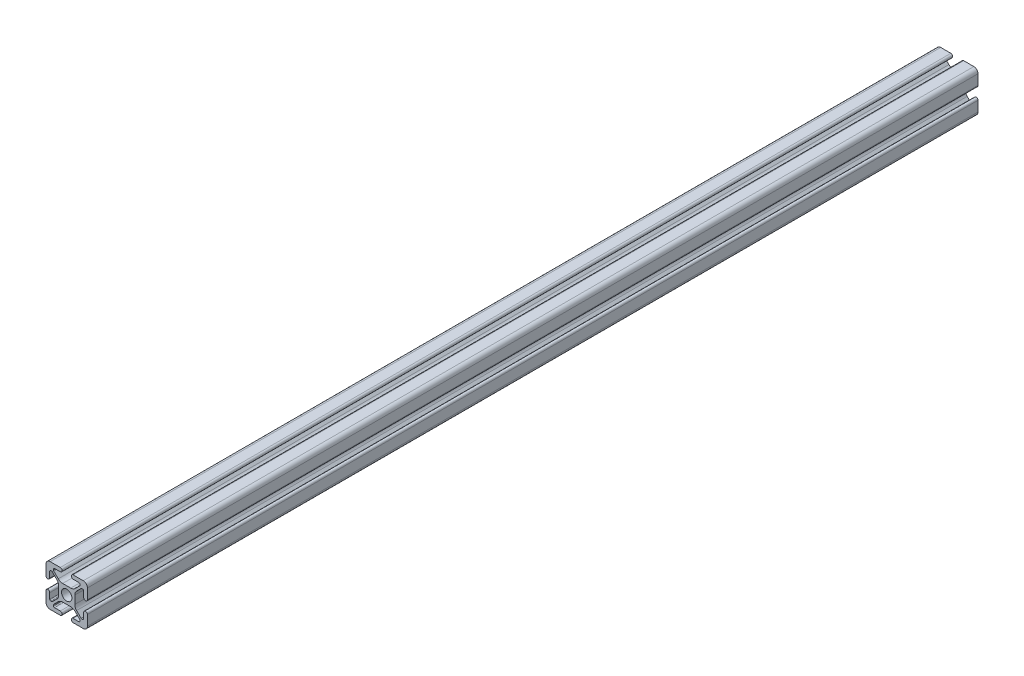
SolidWorks part; units mm, degrees
ref_plane "前视基准面" through (0, 0, 0) normal (0, 0, 1) x (1, 0, 0)
ref_plane "上视基准面" through (0, 0, 0) normal (0, 1, 0) x (1, 0, 0)
ref_plane "右视基准面" through (0, 0, 0) normal (1, 0, 0) x (0, 0, -1)
sketch "草图2" plane through (0, 0, 0) normal (0, 0, 1) x (1, 0, 0)
  line L0 (-1.0428, -10.0859) -> (3.8572, -10.0859)
  line L1 (1.0762, -11.8859) -> (3.8572, -11.8859)
  line L2 (2.8854, -15.3072) -> (0.7226, -13.1443)
  line L3 (2.1786, -16.0141) -> (0.0157, -13.8512)
  line L4 (-3.0428, -12.0859) -> (-3.0428, -16.9859)
  line L5 (-1.2428, -14.2048) -> (-1.2428, -16.9859)
  line L6 (-0.7428, -13.7048) -> (-0.3378, -13.7048)
  line L7 (0.5762, -12.3859) -> (0.5762, -12.7908)
  line L8 (-1.0428, -30.0859) -> (3.8572, -30.0859)
  line L9 (1.0762, -28.2859) -> (3.8572, -28.2859)
  line L10 (2.8854, -24.8645) -> (0.7226, -27.0274)
  line L11 (2.1786, -24.1577) -> (0.0157, -26.3205)
  line L12 (-3.0428, -28.0859) -> (-3.0428, -23.1859)
  line L13 (-1.2428, -25.9669) -> (-1.2428, -23.1859)
  line L14 (-0.7428, -26.4669) -> (-0.3378, -26.4669)
  line L15 (0.5762, -27.7859) -> (0.5762, -27.3809)
  line L16 (14.9572, -10.0859) -> (10.0572, -10.0859)
  line L17 (12.8383, -11.8859) -> (10.0572, -11.8859)
  line L18 (11.029, -15.3072) -> (13.1919, -13.1443)
  line L19 (11.7359, -16.0141) -> (13.8988, -13.8512)
  line L20 (16.9572, -12.0859) -> (16.9572, -16.9859)
  line L21 (15.1572, -14.2048) -> (15.1572, -16.9859)
  line L22 (14.6572, -13.7048) -> (14.2523, -13.7048)
  line L23 (13.3383, -12.3859) -> (13.3383, -12.7908)
  line L24 (14.9572, -30.0859) -> (10.0572, -30.0859)
  line L25 (12.8383, -28.2859) -> (10.0572, -28.2859)
  line L26 (11.029, -24.8645) -> (13.1919, -27.0274)
  line L27 (11.7359, -24.1577) -> (13.8988, -26.3205)
  line L28 (16.9572, -28.0859) -> (16.9572, -23.1859)
  line L29 (15.1572, -25.9669) -> (15.1572, -23.1859)
  line L30 (14.6572, -26.4669) -> (14.2523, -26.4669)
  line L31 (13.3383, -27.7859) -> (13.3383, -27.3809)
  line L32 (5.0068, -16.1859) -> (8.9077, -16.1859)
  line L33 (10.8572, -18.1354) -> (10.8572, -22.0363)
  line L34 (3.0572, -18.1354) -> (3.0572, -22.0363)
  line L35 (5.0068, -23.9859) -> (8.9077, -23.9859)
  circle A0 centre (6.9572, -20.0859) radius 2.5
  arc A1 (2.8854, -15.3072) -> (5.0068, -16.1859) centre (5.0068, -13.1859) ccw
  arc A2 (3.0572, -18.1354) -> (2.1786, -16.0141) centre (0.0572, -18.1354) ccw
  arc A3 (3.8572, -11.8859) -> (3.8572, -10.0859) centre (3.8572, -10.9859) ccw
  arc A4 (0.5762, -12.7908) -> (0.7226, -13.1443) centre (1.0762, -12.7908) ccw
  arc A5 (0.0157, -13.8512) -> (-0.3378, -13.7048) centre (-0.3378, -14.2048) ccw
  arc A6 (-3.0428, -16.9859) -> (-1.2428, -16.9859) centre (-2.1428, -16.9859) ccw
  arc A7 (-1.0428, -10.0859) -> (-3.0428, -12.0859) centre (-1.0428, -12.0859) ccw
  arc A8 (-0.7428, -13.7048) -> (-1.2428, -14.2048) centre (-0.7428, -14.2048) ccw
  arc A9 (1.0762, -11.8859) -> (0.5762, -12.3859) centre (1.0762, -12.3859) ccw
  arc A10 (5.0068, -23.9859) -> (2.8854, -24.8645) centre (5.0068, -26.9859) ccw
  arc A11 (2.1786, -24.1577) -> (3.0572, -22.0363) centre (0.0572, -22.0363) ccw
  arc A12 (3.8572, -30.0859) -> (3.8572, -28.2859) centre (3.8572, -29.1859) ccw
  arc A13 (0.7226, -27.0274) -> (0.5762, -27.3809) centre (1.0762, -27.3809) ccw
  arc A14 (-0.3378, -26.4669) -> (0.0157, -26.3205) centre (-0.3378, -25.9669) ccw
  arc A15 (-1.2428, -23.1859) -> (-3.0428, -23.1859) centre (-2.1428, -23.1859) ccw
  arc A16 (-3.0428, -28.0859) -> (-1.0428, -30.0859) centre (-1.0428, -28.0859) ccw
  arc A17 (-1.2428, -25.9669) -> (-0.7428, -26.4669) centre (-0.7428, -25.9669) ccw
  arc A18 (0.5762, -27.7859) -> (1.0762, -28.2859) centre (1.0762, -27.7859) ccw
  arc A19 (8.9077, -16.1859) -> (11.029, -15.3072) centre (8.9077, -13.1859) ccw
  arc A20 (11.7359, -16.0141) -> (10.8572, -18.1354) centre (13.8572, -18.1354) ccw
  arc A21 (10.0572, -10.0859) -> (10.0572, -11.8859) centre (10.0572, -10.9859) ccw
  arc A22 (13.1919, -13.1443) -> (13.3383, -12.7908) centre (12.8383, -12.7908) ccw
  arc A23 (14.2523, -13.7048) -> (13.8988, -13.8512) centre (14.2523, -14.2048) ccw
  arc A24 (15.1572, -16.9859) -> (16.9572, -16.9859) centre (16.0572, -16.9859) ccw
  arc A25 (16.9572, -12.0859) -> (14.9572, -10.0859) centre (14.9572, -12.0859) ccw
  arc A26 (15.1572, -14.2048) -> (14.6572, -13.7048) centre (14.6572, -14.2048) ccw
  arc A27 (13.3383, -12.3859) -> (12.8383, -11.8859) centre (12.8383, -12.3859) ccw
  arc A28 (11.029, -24.8645) -> (8.9077, -23.9859) centre (8.9077, -26.9859) ccw
  arc A29 (10.8572, -22.0363) -> (11.7359, -24.1577) centre (13.8572, -22.0363) ccw
  arc A30 (10.0572, -28.2859) -> (10.0572, -30.0859) centre (10.0572, -29.1859) ccw
  arc A31 (13.3383, -27.3809) -> (13.1919, -27.0274) centre (12.8383, -27.3809) ccw
  arc A32 (13.8988, -26.3205) -> (14.2523, -26.4669) centre (14.2523, -25.9669) ccw
  arc A33 (16.9572, -23.1859) -> (15.1572, -23.1859) centre (16.0572, -23.1859) ccw
  arc A34 (14.9572, -30.0859) -> (16.9572, -28.0859) centre (14.9572, -28.0859) ccw
  arc A35 (14.6572, -26.4669) -> (15.1572, -25.9669) centre (14.6572, -25.9669) ccw
  arc A36 (12.8383, -28.2859) -> (13.3383, -27.7859) centre (12.8383, -27.7859) ccw
extrude "凸台-拉伸1" add sketch "草图2" along normal blind 430
ref_plane "基准面1" through (0, 0, 215) normal (0, 0, -1) x (-1, 0, 0)
